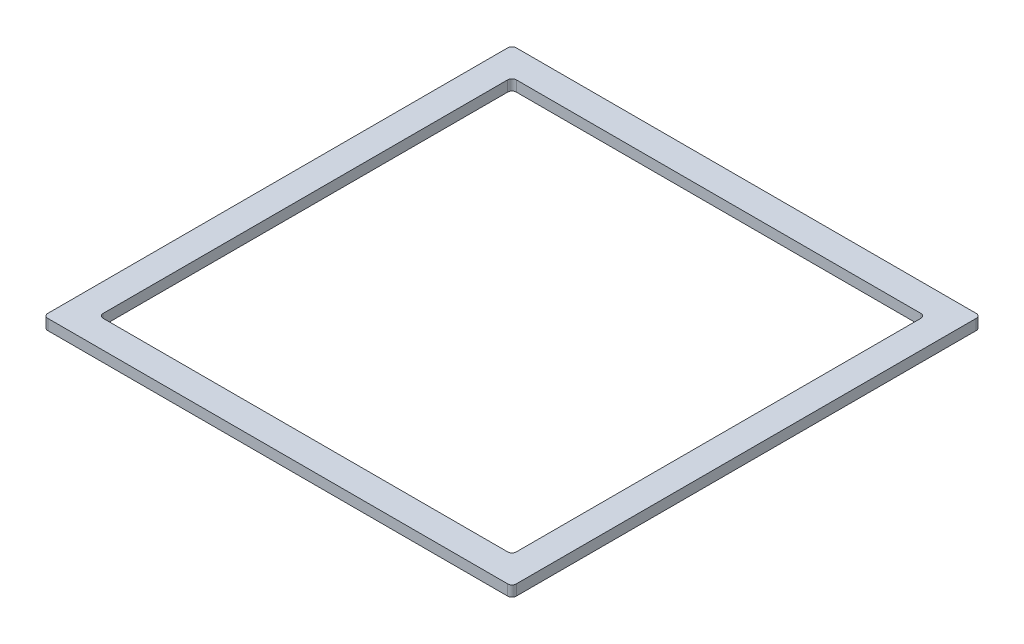
SolidWorks part; units mm, degrees
material "Nylon 101"
ref_plane "Front Plane" through (0, 0, 0) normal (0, 0, 1) x (1, 0, 0)
ref_plane "Top Plane" through (0, 0, 0) normal (0, 1, 0) x (1, 0, 0)
ref_plane "Right Plane" through (0, 0, 0) normal (1, 0, 0) x (0, 0, -1)
sketch "Sketch1" plane through (0, 0, 0) normal (0, 1, 0) x (1, 0, 0)
  line L1 (-97, 97) -> (97, 97)
  line L2 (-97, 97) -> (-97, -97)
  line L3 (-97, -97) -> (97, -97)
  line L4 (97, 97) -> (97, -97)
  line L5 (-97, 97) -> (97, -97) construction
  line L6 (-97, -97) -> (97, 97) construction
  line L7 (-110, 110) -> (110, 110)
  line L8 (-110, 110) -> (-110, -110)
  line L9 (-110, -110) -> (110, -110)
  line L10 (110, 110) -> (110, -110)
  line L11 (-110, 110) -> (110, -110) construction
  line L12 (-110, -110) -> (110, 110) construction
  point P0 (0, 0)
  point P6 (0, 0)
  dimension "D1" = 194
  dimension "D2" = 194
  dimension "D3" = 220
  dimension "D4" = 220
extrude "Boss-Extrude1" add sketch "Sketch1" along normal blind 5
fillet "Fillet1" radius 2 8 edges at (-97, 2.5, -97) (-97, 2.5, 97) (97, 2.5, 97) (97, 2.5, -97) (-110, 2.5, 110) (-110, 2.5, -110) (110, 2.5, -110) (110, 2.5, 110)
